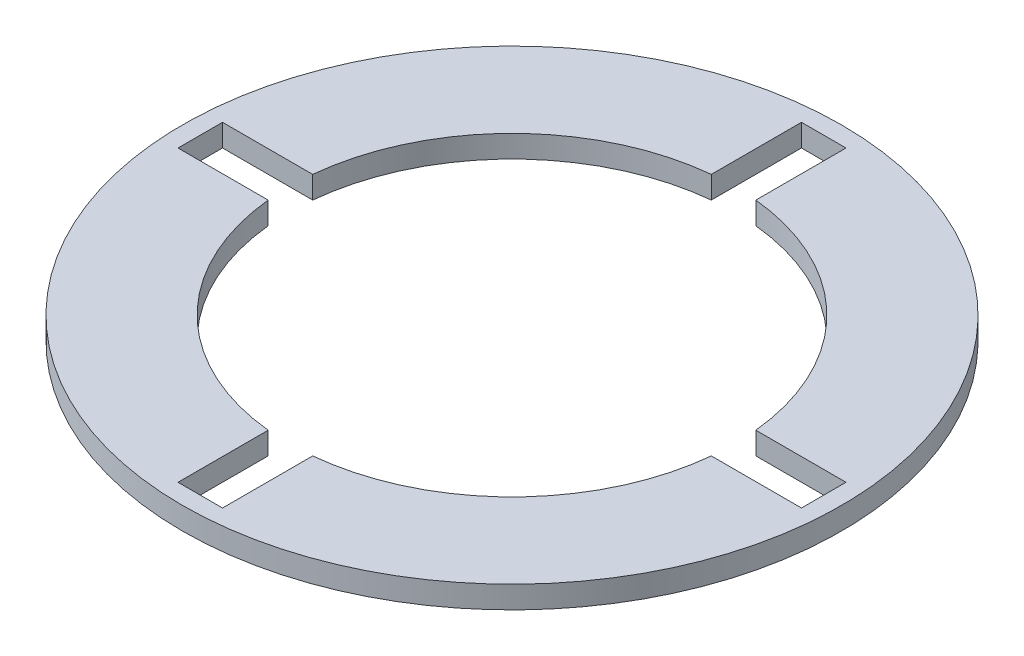
SolidWorks part; units mm, degrees
ref_plane "Front Plane" through (0, 0, 0) normal (0, 0, 1) x (1, 0, 0)
ref_plane "Top Plane" through (0, 0, 0) normal (0, 1, 0) x (1, 0, 0)
ref_plane "Right Plane" through (0, 0, 0) normal (1, 0, 0) x (0, 0, -1)
sketch "Sketch1" plane through (0, 0, 0) normal (0, 1, 0) x (1, 0, 0)
  circle A0 centre (0, 0) radius 46.99
  dimension "D1" = 93.98
extrude "Boss-Extrude1" add sketch "Sketch1" along normal blind 3.175
sketch "Sketch2" plane through (0, 3.175, 0) normal (0, 1, 0) x (1, 0, 0)
  circle A0 centre (0, 0) radius 14.351
  dimension "D1" = 28.702
extrude "Cut-Extrude1" cut sketch "Sketch2" against normal blind 3.175
sketch "Sketch5" plane through (0, 3.175, 0) normal (0, 1, 0) x (1, 0, 0)
  line L1 (3.175, 44.45) -> (-3.175, 44.45)
  line L2 (3.175, 44.45) -> (3.175, -44.45)
  line L3 (3.175, -44.45) -> (-3.175, -44.45)
  line L4 (-3.175, 44.45) -> (-3.175, -44.45)
  line L5 (3.175, 44.45) -> (-3.175, -44.45) construction
  line L6 (3.175, -44.45) -> (-3.175, 44.45) construction
  line L7 (-44.45, 3.175) -> (44.45, 3.175)
  line L8 (-44.45, 3.175) -> (-44.45, -3.175)
  line L9 (-44.45, -3.175) -> (44.45, -3.175)
  line L10 (44.45, 3.175) -> (44.45, -3.175)
  line L11 (-44.45, 3.175) -> (44.45, -3.175) construction
  line L12 (-44.45, -3.175) -> (44.45, 3.175) construction
  point P0 (0, 0)
  point P6 (0, 0)
  circle M1 centre (0, 0) radius 14.351
  dimension "D1" = 6.35
  dimension "D2" = 88.9
  dimension "D3" = 88.9
  dimension "D4" = 6.35
extrude "Cut-Extrude2" cut sketch "Sketch5" against normal blind 7.62 contours L1 L4 L2 M1 | L4 L3 L2 M1 | L8 L9 L7 M1 | L10 L7 L9 M1
sketch "Sketch6" plane through (0, 3.175, 0) normal (0, 1, 0) x (1, 0, 0)
  circle A0 centre (0, 0) radius 31.75
  dimension "D1" = 63.5
extrude "Cut-Extrude3" cut sketch "Sketch6" against normal blind 5.08
